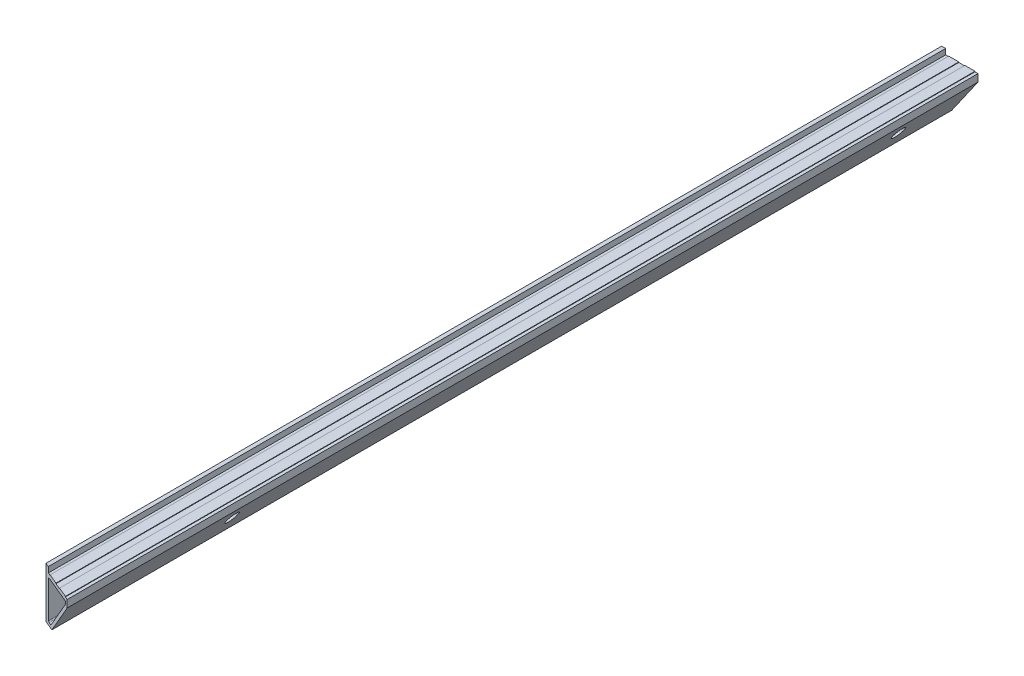
SolidWorks part; units mm, degrees
ref_plane "前视基准面" through (0, 0, 0) normal (0, 0, 1) x (1, 0, 0)
ref_plane "上视基准面" through (0, 0, 0) normal (0, 1, 0) x (1, 0, 0)
ref_plane "右视基准面" through (0, 0, 0) normal (1, 0, 0) x (0, 0, -1)
sketch "草图1" plane through (0, 0, 0) normal (0, 0, 1) x (1, 0, 0)
  line L0 (36, -0.5) -> (36, -7.8426)
  line L1 (7, 0) -> (17, 0)
  line L2 (0, 0) -> (0, -45)
  line L3 (0, -45) -> (10, -45)
  line L4 (36, -7.8426) -> (10, -45)
  line L5 (0, 0) -> (0, 5)
  line L7 (33, -5) -> (33, -6.5821)
  line L8 (32.8193, -7.1554) -> (8.7362, -41.5733)
  line L9 (5.5, -42) -> (7.9169, -42)
  line L10 (33, -3) -> (33, -6.8973) construction
  line L11 (5.5, -4) -> (32, -4)
  line L12 (3, -42) -> (8.4377, -42) construction
  line L14 (4, -0.5) -> (4, 5)
  line L15 (4.5, -5) -> (4.5, -41)
  line L16 (0, 0) -> (36, 0) construction
  line L17 (3, -3) -> (33, -3) construction
  line L18 (3, -3) -> (3, -42) construction
  line L22 (0, 5) -> (4, 5)
  line L23 (4, -0.5) -> (7, -0.5)
  line L24 (33, -6.8973) -> (8.4377, -42) construction
  line L25 (33, -0.5) -> (33, 0)
  line L26 (23, -0.5) -> (23, 0)
  line L27 (17, -0.5) -> (17, 0)
  line L28 (7, -0.5) -> (7, 0)
  line L29 (7, 0) -> (7, 8.4394) construction
  line L30 (33, 0) -> (33, 8.4394) construction
  line L31 (35.5, -0.5) -> (35.5, -7.6851) construction
  line L32 (35.5, -7.6851) -> (9.7396, -44.5) construction
  line L33 (0.5, 0) -> (0.5, 4.5) construction
  line L34 (3.5, -0.5) -> (3.5, 4.5) construction
  line L35 (0.5, 0) -> (0.5, -44.5) construction
  line L36 (0.5, 4.5) -> (3.5, 4.5) construction
  line L37 (0.5, -44.5) -> (9.7396, -44.5) construction
  line L38 (23, 0) -> (23, 8.4394) construction
  line L39 (17, 0) -> (17, 8.4394) construction
  line L40 (4, 0) -> (36, 0) construction
  line L41 (3.5, -0.5) -> (35.5, -0.5) construction
  line L42 (4, 0) -> (4, 5) construction
  line L43 (23, 0) -> (33, 0)
  line L44 (17, -0.5) -> (23, -0.5)
  line L45 (33, -0.5) -> (36, -0.5)
  line L46 (36, 0) -> (36, -7.8426) construction
  arc A0 (8.7362, -41.5733) -> (7.9169, -42) centre (7.9169, -41) cw
  arc A1 (4.5, -41) -> (5.5, -42) centre (5.5, -41) ccw
  arc A2 (33, -6.5821) -> (32.8193, -7.1554) centre (32, -6.5821) cw
  arc A3 (33, -5) -> (32, -4) centre (32, -5) ccw
  arc A4 (5.5, -4) -> (4.5, -5) centre (5.5, -5) ccw
  dimension "D3" = 1
  dimension "D15" = 4.5
  dimension "D2" = 45
  dimension "D4" = 10
  dimension "D5" = 5
  dimension "D9" = 0.5
  dimension "D10" = 32
  dimension "D14" = 3
  dimension "D7" = 4
  dimension "D16" = 34.981
  dimension "D6" = 3
  dimension "D8" = 4
  dimension "D11" = 10
  dimension "D12" = 6
  dimension "D13" = 10
extrude "凸台-拉伸1" add sketch "草图1" along normal blind 901
hole_wizard "Ø7.0 (7) 直径孔1" positions "草图3" profile "草图2" hole size "Ø7.0" standard "GB" end condition through all
sketch "草图3" plane through (0, 0, 0) normal (-1, 0, 0) x (0, 0, 1)
  line L0 (0, 5) -> (0, -45) construction
  line L1 (901, 5) -> (0, 5) construction
  point P0 (68.68, -22)
  point P1 (727.88, -22)
  dimension "D1" = 68.68
  dimension "D2" = 659.2
  dimension "D3" = 27
sketch "草图2" plane through (0, -22, 68.68) normal (0, 1, 0) x (0, 0, 1)
  line L0 (0, 0) -> (0, 36)
  line L1 (0, 36) -> (3.5, 36)
  line L2 (3.5, 36) -> (3.5, 0)
  line L5 (3.5, 0) -> (0, 0)
  line L11 (0, -6.35) -> (0, 107.95) construction
  dimension "通孔孔直径" = 7
  dimension "通孔孔深度" = 36
sketch "草图5" plane through (36, 0, 0) normal (1, 0, 0) x (0, 0, -1)
  line L4 (-68.68, -13.8215) -> (-68.68, -30.3235) construction
  circle A0 centre (-68.68, -22.0725) radius 6
  circle A1 centre (-727.88, -22) radius 6
  dimension "D1" = 12
  dimension "D2" = 12
extrude "切除-拉伸2" cut sketch "草图5" against normal up to surface (13.5678 mm away)
hole_wizard "M5 螺纹孔1" positions "草图7" profile "草图6" tap size "M5" standard "GB"
sketch "草图7" plane through (0, 0, 0) normal (-1, 0, 0) x (0, 0, 1)
  point P0 (18.6366, -11.936)
  point P1 (18.6366, -32)
  point P3 (118.6756, -11.936)
  point P5 (118.6756, -32)
sketch "草图6" plane through (0, -11.936, 18.6366) normal (0, 1, 0) x (0, 0, 1)
  line L0 (0, 0) -> (0, 4.5)
  line L1 (0, 4.5) -> (2.5, 4.5)
  line L2 (2.5, 4.5) -> (2.5, 0)
  line L5 (2.5, 0) -> (0, 0)
  line L11 (0, -6.35) -> (0, 107.95) construction
  dimension "螺纹线主直径" = 5
  dimension "通孔螺纹孔钻头深度" = 4.5
hole_wizard "M5 螺纹孔2" positions "草图9" profile "草图8" tap size "M5" standard "GB"
sketch "草图9" plane through (0, 0, 0) normal (-1, 0, 0) x (0, 0, 1)
  line L0 (727.88, -3.198) -> (727.88, -40.753) construction
  line L2 (859.6802, -22) -> (928.2498, -22) construction
  point P0 (703.88, -12)
  point P1 (751.88, -12)
  point P3 (751.88, -32)
  point P5 (703.88, -32)
  dimension "D1" = 20
  dimension "D2" = 48
sketch "草图8" plane through (0, -12, 703.88) normal (0, 1, 0) x (0, 0, 1)
  line L0 (0, 0) -> (0, 4.5)
  line L1 (0, 4.5) -> (2.5, 4.5)
  line L2 (2.5, 4.5) -> (2.5, 0)
  line L5 (2.5, 0) -> (0, 0)
  line L11 (0, -6.35) -> (0, 107.95) construction
  dimension "螺纹线主直径" = 5
  dimension "通孔螺纹孔钻头深度" = 4.5
sketch "草图11" plane through (0, 5, 0) normal (0, 1, 0) x (1, 0, 0)
  line L0 (36, -901) -> (0, -885.9409)
  line L1 (0, -901) -> (36, -901)
  line L2 (0, -901) -> (0, -885.9409)
  line L3 (0, -901) -> (0, 0) construction
  dimension "D1" = 22.7
extrude "切除-拉伸3" cut sketch "草图11" against normal through all
